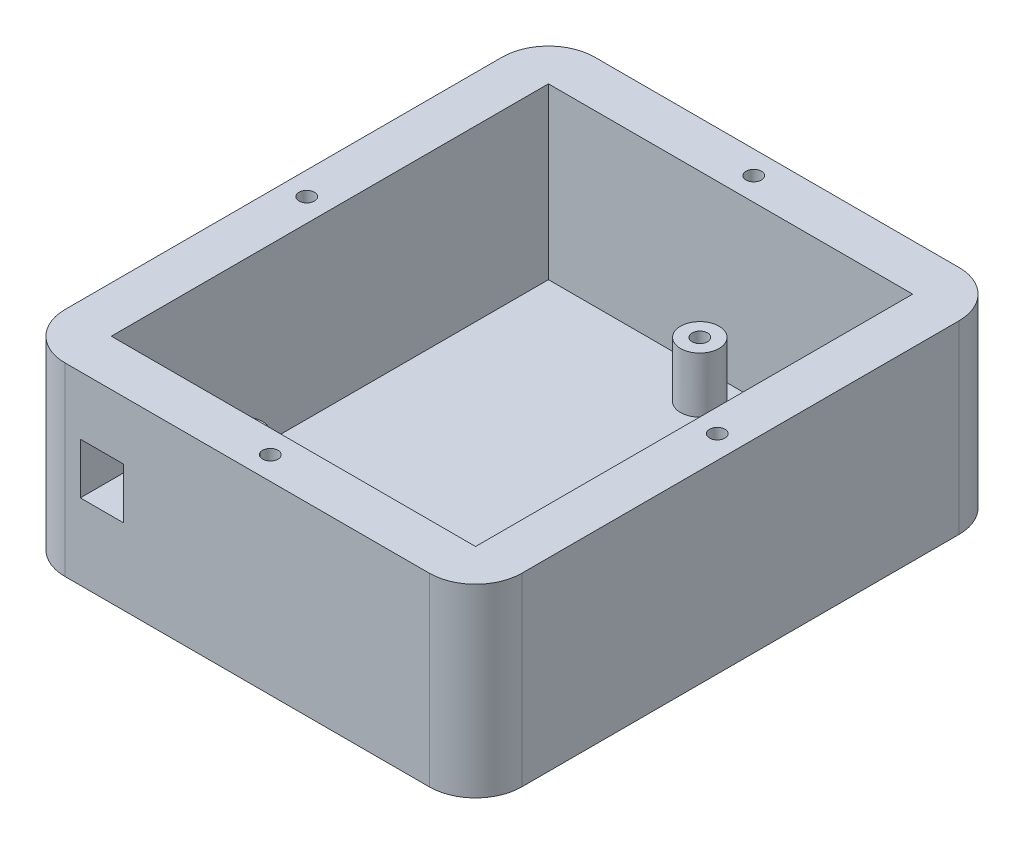
SolidWorks part; units mm, degrees
ref_plane "Front Plane" through (0, 0, 0) normal (0, 0, 1) x (1, 0, 0)
ref_plane "Top Plane" through (0, 0, 0) normal (0, 1, 0) x (1, 0, 0)
ref_plane "Right Plane" through (0, 0, 0) normal (1, 0, 0) x (0, 0, -1)
sketch "Sketch1" plane through (0, 0, 0) normal (0, 1, 0) x (1, 0, 0)
  line L1 (3.175, 0) -> (78.175, 0)
  line L2 (0, 3.175) -> (0, 93.175)
  line L3 (3.175, 96.35) -> (78.175, 96.35)
  line L4 (81.35, 3.175) -> (81.35, 93.175)
  arc A0 (3.175, 0) -> (0, 3.175) centre (3.175, 3.175) cw
  arc A1 (78.175, 0) -> (81.35, 3.175) centre (78.175, 3.175) ccw
  arc A2 (78.175, 96.35) -> (81.35, 93.175) centre (78.175, 93.175) cw
  arc A3 (0, 93.175) -> (3.175, 96.35) centre (3.175, 93.175) cw
  point P7 (0, 0)
  point P10 (81.35, 0)
  point P13 (81.35, 96.35)
  dimension "D3" = 3.175
  dimension "D1" = 81.35
  dimension "D2" = 96.35
extrude "Boss-Extrude1" add sketch "Sketch1" along normal blind 38.1
sketch "Sketch2" plane through (0, 38.1, 0) normal (0, 1, 0) x (1, 0, 0)
  line L8 (3.175, 3.175) -> (78.175, 3.175)
  line L9 (78.175, 3.175) -> (78.175, 93.175)
  line L10 (78.175, 93.175) -> (3.175, 93.175)
  line L11 (3.175, 93.175) -> (3.175, 3.175)
  line L12 (3.175, 3.175) -> (78.175, 3.175)
  line L13 (78.175, 3.175) -> (78.175, 93.175)
  line L14 (78.175, 93.175) -> (3.175, 93.175)
  line L15 (3.175, 93.175) -> (3.175, 3.175)
  dimension "D1" = 3.175
extrude "Cut-Extrude1" cut sketch "Sketch2" against normal offset from surface (34.925 mm away) 3.175 up to face at (40.675, 0, -48.175)
sketch "Sketch3" plane through (0, 3.175, 0) normal (0, 1, 0) x (1, 0, 0)
  line L0 (3.175, 93.175) -> (3.175, 3.175) construction
  line L1 (4.575, 92.05) -> (76.775, 92.05) construction
  line L2 (4.575, 92.05) -> (4.575, 4.3) construction
  line L3 (4.575, 4.3) -> (76.775, 4.3) construction
  line L4 (76.775, 92.05) -> (76.775, 4.3) construction
  line L5 (78.175, 93.175) -> (3.175, 93.175) construction
  circle A0 centre (10.465, 23.05) radius 1.5875
  circle A1 centre (40.465, 87.05) radius 1.5875
  circle A2 centre (40.465, 87.05) radius 3.9687
  circle A3 centre (10.465, 23.05) radius 3.9687
  point P6 (3.175, 48.175)
  point P7 (4.575, 48.175)
  point P10 (40.675, 93.175)
  point P11 (40.675, 92.05)
  dimension "D3" = 3.175
  dimension "D8" = 7.9375
  dimension "D9" = 7.9375
  dimension "D1" = 72.2
  dimension "D2" = 87.75
  dimension "D4" = 18.75
  dimension "D5" = 5.89
  dimension "D6" = 82.75
  dimension "D7" = 35.89
extrude "Boss-Extrude2" add sketch "Sketch3" along normal blind 11.43
sketch "Sketch4" plane through (0, 0, 0) normal (0, -1, 0) x (1, 0, 0)
  line L0 (-6.35, -3.175) -> (-6.35, -93.175)
  line L1 (3.175, -102.7) -> (78.175, -102.7)
  line L2 (87.7, -93.175) -> (87.7, -3.175)
  line L3 (78.175, 6.35) -> (3.175, 6.35)
  line L4 (0, -3.175) -> (0, -93.175)
  line L5 (3.175, -96.35) -> (78.175, -96.35)
  line L6 (81.35, -93.175) -> (81.35, -3.175)
  line L7 (78.175, 0) -> (3.175, 0)
  line L8 (0, -3.175) -> (0, -93.175)
  line L9 (3.175, -96.35) -> (78.175, -96.35)
  line L10 (81.35, -93.175) -> (81.35, -3.175)
  line L11 (78.175, 0) -> (3.175, 0)
  arc A0 (3.175, 6.35) -> (-6.35, -3.175) centre (3.175, -3.175) ccw
  arc A1 (-6.35, -93.175) -> (3.175, -102.7) centre (3.175, -93.175) ccw
  arc A2 (78.175, -102.7) -> (87.7, -93.175) centre (78.175, -93.175) ccw
  arc A3 (87.7, -3.175) -> (78.175, 6.35) centre (78.175, -3.175) ccw
  arc A4 (3.175, 0) -> (0, -3.175) centre (3.175, -3.175) ccw
  arc A5 (0, -93.175) -> (3.175, -96.35) centre (3.175, -93.175) ccw
  arc A6 (78.175, -96.35) -> (81.35, -93.175) centre (78.175, -93.175) ccw
  arc A7 (81.35, -3.175) -> (78.175, 0) centre (78.175, -3.175) ccw
  arc A8 (3.175, 0) -> (0, -3.175) centre (3.175, -3.175) ccw
  arc A9 (0, -93.175) -> (3.175, -96.35) centre (3.175, -93.175) ccw
  arc A10 (78.175, -96.35) -> (81.35, -93.175) centre (78.175, -93.175) ccw
  arc A11 (81.35, -3.175) -> (78.175, 0) centre (78.175, -3.175) ccw
  dimension "D1" = 0
  dimension "D2" = 6.35
extrude "Boss-Extrude3" add sketch "Sketch4" against normal up to surface (38.1 mm away) up to face at (40.675, 38.1, -48.175)
sketch "Sketch5" plane through (0, 38.1, 0) normal (0, 1, 0) x (1, 0, 0)
  line L0 (-6.35, 48.175) -> (3.175, 48.175) construction
  line L1 (-6.35, 93.175) -> (-6.35, 3.175) construction
  line L2 (3.175, 93.175) -> (3.175, 3.175) construction
  line L3 (40.675, 102.7) -> (40.675, 93.175) construction
  line L4 (78.175, 102.7) -> (3.175, 102.7) construction
  line L5 (78.175, 93.175) -> (3.175, 93.175) construction
  line L6 (40.675, 93.175) -> (40.675, -1.5718) construction
  line L7 (40.675, -1.5718) -> (3.175, 48.175) construction
  line L8 (3.175, 48.175) -> (78.175, 48.175) construction
  line L9 (78.175, 3.175) -> (78.175, 93.175) construction
  circle A0 centre (-1.5875, 48.175) radius 1.5875
  circle A1 centre (40.675, 97.9375) radius 1.5875
  circle A2 centre (40.675, -1.5875) radius 1.5875
  circle A3 centre (82.9375, 48.175) radius 1.5875
  point P16 (40.675, 97.9375)
  point P17 (-1.5875, 48.175)
  dimension "D1" = 3.175
  dimension "D2" = 3.175
extrude "Cut-Extrude2" cut sketch "Sketch5" against normal blind 12.7
sketch "Sketch8" [suppressed] plane through (0, 38.1, 0) normal (0, 1, 0) x (1, 0, 0)
  line L4 (3.175, -6.35) -> (78.175, -6.35)
  line L5 (87.7, 3.175) -> (87.7, 93.175)
  line L6 (78.175, 102.7) -> (3.175, 102.7)
  line L7 (-6.35, 93.175) -> (-6.35, 3.175)
  line L8 (3.175, -6.35) -> (78.175, -6.35)
  line L9 (87.7, 3.175) -> (87.7, 93.175)
  line L10 (78.175, 102.7) -> (3.175, 102.7)
  line L11 (-6.35, 93.175) -> (-6.35, 3.175)
  circle A0 centre (40.675, -1.5875) radius 1.5875 construction
  circle A1 centre (-1.5875, 48.175) radius 1.5875
  circle A2 centre (-1.5875, 48.175) radius 1.5875
  circle A3 centre (82.9375, 48.175) radius 1.5875 construction
  circle A4 centre (40.675, 97.9375) radius 1.5875 construction
  circle A5 centre (40.675, -1.5875) radius 1.5875
  circle A6 centre (82.9375, 48.175) radius 1.5875
  circle A7 centre (40.675, 97.9375) radius 1.5875
  arc A12 (-6.35, 3.175) -> (3.175, -6.35) centre (3.175, 3.175) ccw
  arc A13 (78.175, -6.35) -> (87.7, 3.175) centre (78.175, 3.175) ccw
  arc A14 (87.7, 93.175) -> (78.175, 102.7) centre (78.175, 93.175) ccw
  arc A15 (3.175, 102.7) -> (-6.35, 93.175) centre (3.175, 93.175) ccw
  arc A16 (-6.35, 3.175) -> (3.175, -6.35) centre (3.175, 3.175) ccw
  arc A17 (78.175, -6.35) -> (87.7, 3.175) centre (78.175, 3.175) ccw
  arc A18 (87.7, 93.175) -> (78.175, 102.7) centre (78.175, 93.175) ccw
  arc A19 (3.175, 102.7) -> (-6.35, 93.175) centre (3.175, 93.175) ccw
  dimension "D1" = 0
  dimension "D2" = 0
sketch "Sketch9" plane through (0, 0, 6.35) normal (0, 0, 1) x (1, 0, 0)
  line L0 (10.765, 38.1) -> (10.765, 0) construction
  line L1 (3.175, 38.1) -> (78.175, 38.1) construction
  line L2 (78.175, 0) -> (3.175, 0) construction
  line L4 (12.0525, 14.605) -> (8.8775, 14.605) construction
  line L5 (12.0525, 14.605) -> (8.8775, 14.605) construction
  line L6 (6.32, 26.0825) -> (15.21, 26.0825)
  line L7 (6.32, 26.0825) -> (6.32, 15.605)
  line L8 (6.32, 15.605) -> (15.21, 15.605)
  line L9 (15.21, 26.0825) -> (15.21, 15.605)
  point P8 (10.465, 14.605)
  point P13 (10.765, 15.605)
  dimension "D2" = 8.89
  dimension "D3" = 10.4775
  dimension "D1" = 0.3
  dimension "D4" = 1
extrude "Cut-Extrude3" cut sketch "Sketch9" against normal up to surface (9.525 mm away) up to face at (40.675, 20.6375, -3.175)
